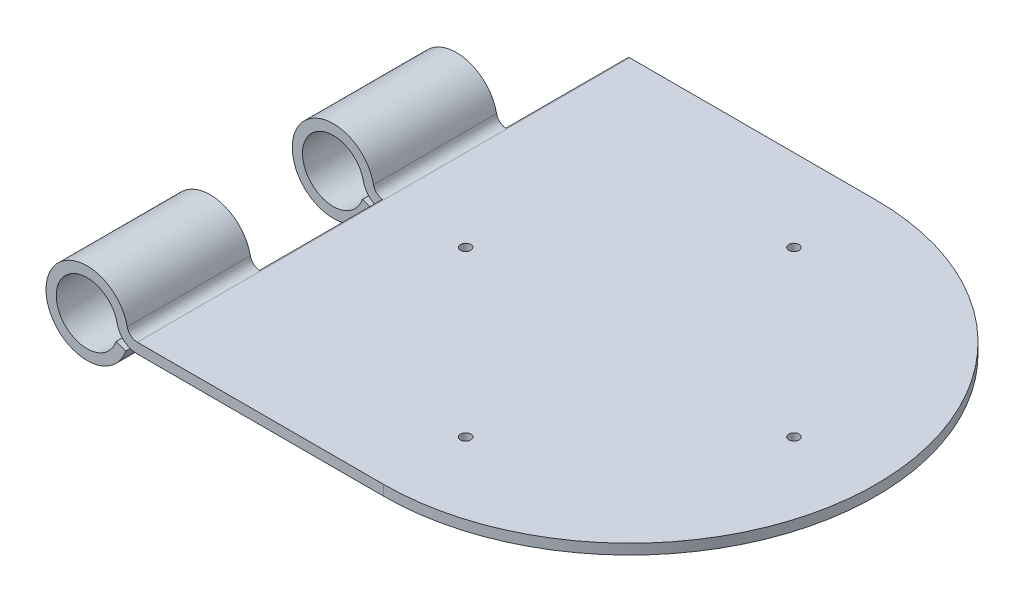
SolidWorks part; units mm, degrees
ref_plane "Front Plane" through (0, 0, 0) normal (0, 0, 1) x (1, 0, 0)
ref_plane "Top Plane" through (0, 0, 0) normal (0, 1, 0) x (1, 0, 0)
ref_plane "Right Plane" through (0, 0, 0) normal (1, 0, 0) x (0, 0, -1)
sketch "Sketch1" plane through (0, 0, 0) normal (0, 0, 1) x (1, 0, 0)
  line L2 (6.0067, -2.0597) -> (4.505, -1.5448)
  line L3 (7.7771, 0) -> (83.9771, 0)
  line L5 (7.7771, -1.5875) -> (83.9771, -1.5875)
  line L6 (83.9771, 0) -> (83.9771, -1.5875)
  arc A0 (6.2217, 1.27) -> (6.0067, -2.0597) centre (0, 0) ccw
  arc A1 (4.6663, 0.9525) -> (4.505, -1.5448) centre (0, 0) ccw
  arc A2 (6.2217, 1.27) -> (7.7771, 0) centre (7.7771, 1.5875) ccw
  arc A3 (7.7771, -1.5875) -> (4.6663, 0.9525) centre (7.7771, 1.5875) cw
  dimension "D3" = 9.525
  dimension "D4" = 1.5875
  dimension "D5" = 1.5875
  dimension "D2" = 3.175
  dimension "D1" = 1.5875
  dimension "D6" = 76.2
extrude "Boss-Extrude1" add sketch "Sketch1" along normal blind 76.2
sketch "Sketch2" plane through (69.85, -1.5875, 0) normal (0, 1, 0) x (0, 0, -1)
  line L1 (0, 62.23) -> (-19.05, 62.23)
  line L2 (0, 62.23) -> (0, 76.2)
  line L3 (0, 76.2) -> (-19.05, 76.2)
  line L4 (-19.05, 62.23) -> (-19.05, 76.2)
  line L6 (-57.15, 62.23) -> (-38.1, 62.23)
  line L7 (-57.15, 62.23) -> (-57.15, 76.2)
  line L8 (-57.15, 76.2) -> (-38.1, 76.2)
  line L9 (-38.1, 62.23) -> (-38.1, 76.2)
  line L10 (-76.2, 76.2) -> (-76.2, 63.6283) construction
  line L11 (0, 76.2) -> (-76.2, 76.2) construction
  dimension "D1" = 19.05
  dimension "D2" = 19.05
  dimension "D3" = 19.05
  dimension "D4" = 13.97
extrude "Cut-Extrude1" cut sketch "Sketch2" along normal through all and the other way through all
sketch "Sketch3" plane through (0, -1.5875, 0) normal (0, 1, 0) x (1, 0, 0)
  line L2 (45.8771, 0) -> (83.9771, 0)
  line L3 (83.9771, 0) -> (83.9771, -76.2)
  line L4 (83.9771, -76.2) -> (45.8771, -76.2)
  line L6 (83.9771, -76.2) -> (83.9771, 0) construction
  line L7 (7.7771, 0) -> (83.9771, 0) construction
  line L8 (7.7771, -76.2) -> (83.9771, -76.2) construction
  arc A0 (45.8771, -76.2) -> (45.8771, 0) centre (45.8771, -38.1) ccw
  circle A1 centre (71.2771, -38.1) radius 0.7937
  circle A2 centre (45.8771, -12.7) radius 0.7937
  circle A3 centre (45.8771, -63.5) radius 0.7937
  circle A4 centre (45.8771, -38.1) radius 25.4 construction
  circle A5 centre (20.4771, -38.1) radius 0.7937
  line M28 (7.7771, 0) -> (83.9771, 0)
  line M29 (83.9771, 0) -> (83.9771, -76.2)
  line M30 (83.9771, -76.2) -> (7.7771, -76.2)
  dimension "D1" = 76.2
  dimension "D2" = 1.5875
  dimension "D3" = 50.8
extrude "Cut-Extrude2" cut sketch "Sketch3" along normal through all contours A0 M29 M28 | A0 L3 M30 | A3 | A5 | A1 | A2
